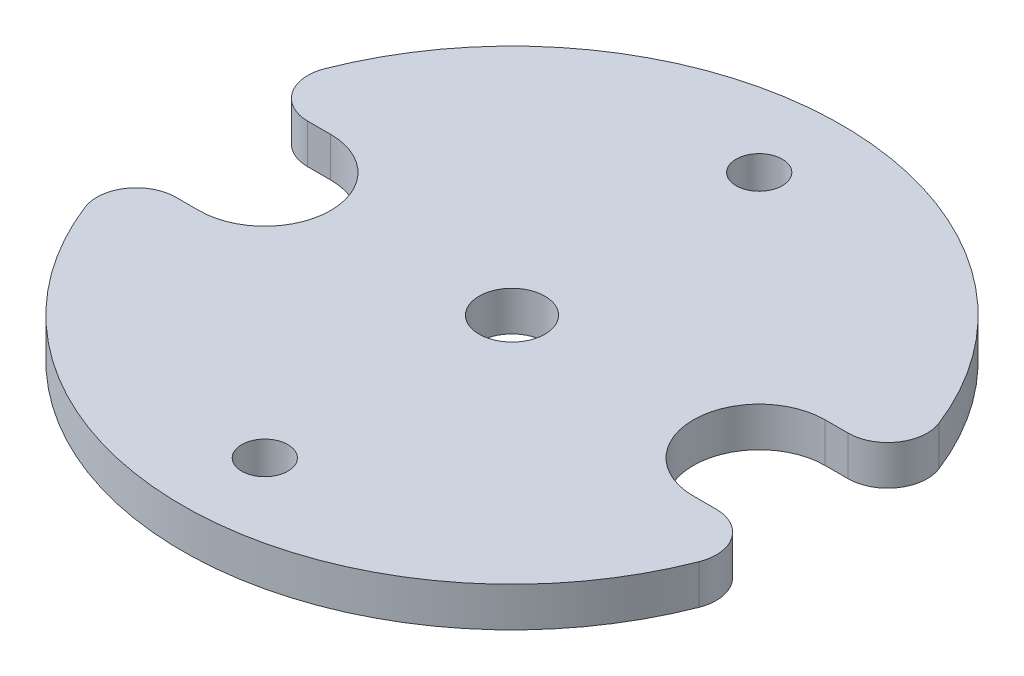
SolidWorks part; units mm, degrees
ref_plane "Front Plane" through (0, 0, 0) normal (0, 0, 1) x (1, 0, 0)
ref_plane "Top Plane" through (0, 0, 0) normal (0, 1, 0) x (1, 0, 0)
ref_plane "Right Plane" through (0, 0, 0) normal (1, 0, 0) x (0, 0, -1)
sketch "Sketch1" plane through (0, 0, 0) normal (0, 1, 0) x (1, 0, 0)
  line L0 (-28.8378, 5.5817) -> (-30.6096, 5.5817)
  line L1 (-28.8378, -4.5783) -> (-30.6096, -4.5783)
  line L2 (9.2622, -4.5783) -> (11.034, -4.5783)
  line L3 (9.2622, 5.5817) -> (11.034, 5.5817)
  arc A0 (-33.449, -8.7347) -> (13.8733, -8.7347) centre (-9.7878, 0.5017) ccw
  circle A1 centre (-9.7878, 0.5017) radius 19.05 construction
  circle A2 centre (-9.7878, 19.5517) radius 1.778
  arc A3 (-28.8378, -4.5783) -> (-28.8378, 5.5817) centre (-28.8378, 0.5017) ccw
  arc A4 (9.2622, 5.5817) -> (9.2622, -4.5783) centre (9.2622, 0.5017) ccw
  arc A5 (13.8733, 9.738) -> (-33.449, 9.738) centre (-9.7878, 0.5017) ccw
  circle A6 centre (-9.7878, -18.5483) radius 1.778
  arc A7 (11.034, -4.5783) -> (13.8733, -8.7347) centre (11.034, -7.6263) cw
  arc A8 (11.034, 5.5817) -> (13.8733, 9.738) centre (11.034, 8.6297) ccw
  arc A9 (-30.6096, -4.5783) -> (-33.449, -8.7347) centre (-30.6096, -7.6263) ccw
  arc A10 (-30.6096, 5.5817) -> (-33.449, 9.738) centre (-30.6096, 8.6297) cw
  circle A11 centre (-9.7878, 0.5017) radius 2.54
  point P16 (-9.7878, 0.5017)
  point P20 (-9.7878, 0.5017)
  dimension "D1" = 50.8
  dimension "D2" = 38.1
  dimension "D3" = 3.556
  dimension "D4" = 10.16
  dimension "D7" = 3.048
  dimension "D8" = 5.08
  dimension "D5" = 2
  dimension "D6" = 2
extrude "Boss-Extrude1" add sketch "Sketch1" along normal blind 3.048 contours A5 A10 L0 A3 L1 A9 A0 A7 L2 A4 L3 A8
